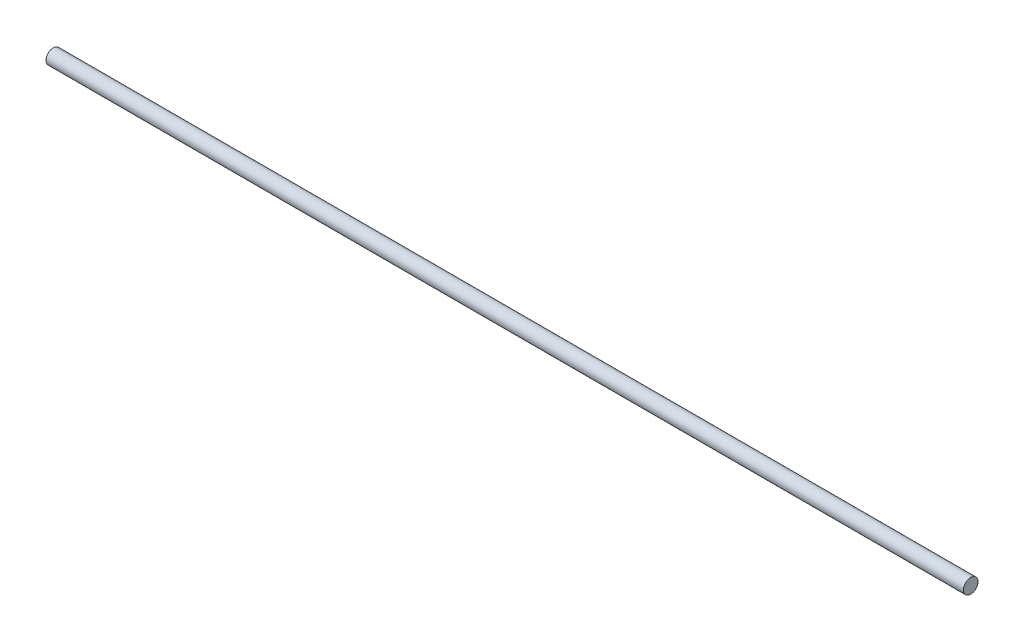
SolidWorks part; units mm, degrees
ref_plane "Front Plane" through (0, 0, 0) normal (0, 0, 1) x (1, 0, 0)
ref_plane "Top Plane" through (0, 0, 0) normal (0, 1, 0) x (1, 0, 0)
ref_plane "Right Plane" through (0, 0, 0) normal (1, 0, 0) x (0, 0, -1)
sketch "Sketch1" plane through (0, 0, 0) normal (1, 0, 0) x (0, 0, -1)
  circle A0 centre (0, 0) radius 10
  dimension "D1" = 20
extrude "Boss-Extrude1" add sketch "Sketch1" along normal blind 1260
